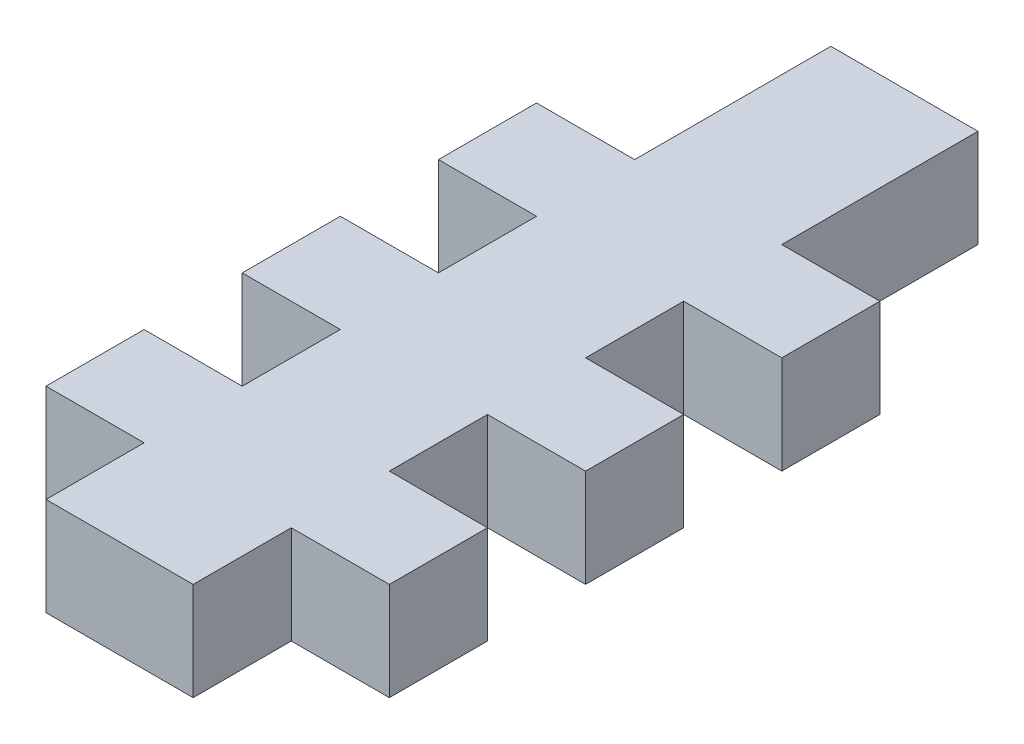
SolidWorks part; units mm, degrees
material "Balsa"
ref_plane "Front Plane" through (0, 0, 0) normal (0, 0, 1) x (1, 0, 0)
ref_plane "Top Plane" through (0, 0, 0) normal (0, 1, 0) x (1, 0, 0)
ref_plane "Right Plane" through (0, 0, 0) normal (1, 0, 0) x (0, 0, -1)
sketch "Sketch1" plane through (0, 0, 0) normal (0, 1, 0) x (1, 0, 0)
  line L0 (0, 0) -> (19.05, 0)
  line L1 (19.05, 0) -> (19.05, 12.7)
  line L2 (19.05, 12.7) -> (31.75, 12.7)
  line L3 (31.75, 12.7) -> (31.75, 25.4)
  line L4 (31.75, 25.4) -> (19.05, 25.4)
  line L5 (19.05, 25.4) -> (19.05, 38.1)
  line L6 (19.05, 38.1) -> (31.75, 38.1)
  line L7 (31.75, 38.1) -> (31.75, 50.8)
  line L8 (31.75, 50.8) -> (19.05, 50.8)
  line L9 (19.05, 50.8) -> (19.05, 63.5)
  line L10 (19.05, 63.5) -> (31.75, 63.5)
  line L11 (31.75, 63.5) -> (31.75, 76.2)
  line L12 (31.75, 76.2) -> (19.05, 76.2)
  line L13 (19.05, 76.2) -> (19.05, 101.6)
  line L14 (19.05, 101.6) -> (0, 101.6)
  line L15 (0, 101.6) -> (0, 76.2)
  line L16 (0, 76.2) -> (-12.7, 76.2)
  line L17 (-12.7, 76.2) -> (-12.7, 63.5)
  line L18 (-12.7, 63.5) -> (0, 63.5)
  line L19 (0, 63.5) -> (0, 50.8)
  line L20 (0, 50.8) -> (-12.7, 50.8)
  line L21 (-12.7, 50.8) -> (-12.7, 38.1)
  line L22 (-12.7, 38.1) -> (0, 38.1)
  line L23 (0, 38.1) -> (0, 25.4)
  line L24 (0, 25.4) -> (-12.7, 25.4)
  line L25 (-12.7, 25.4) -> (-12.7, 12.7)
  line L26 (-12.7, 12.7) -> (0, 12.7)
  line L27 (0, 12.7) -> (0, 0)
  dimension "D1" = 12.7
  dimension "D2" = 12.7
  dimension "D3" = 12.7
  dimension "D4" = 12.7
  dimension "D5" = 12.7
  dimension "D6" = 12.7
  dimension "D7" = 12.7
  dimension "D8" = 12.7
  dimension "D9" = 12.7
  dimension "D10" = 12.7
  dimension "D11" = 12.7
  dimension "D12" = 12.7
  dimension "D13" = 12.7
  dimension "D14" = 12.7
  dimension "D15" = 12.7
  dimension "D16" = 12.7
  dimension "D17" = 12.7
  dimension "D18" = 101.6
  dimension "D19" = 12.7
  dimension "D20" = 12.7
  dimension "D21" = 12.7
  dimension "D22" = 12.7
  dimension "D23" = 19.05
extrude "Boss-Extrude1" add sketch "Sketch1" along normal blind 12.7
